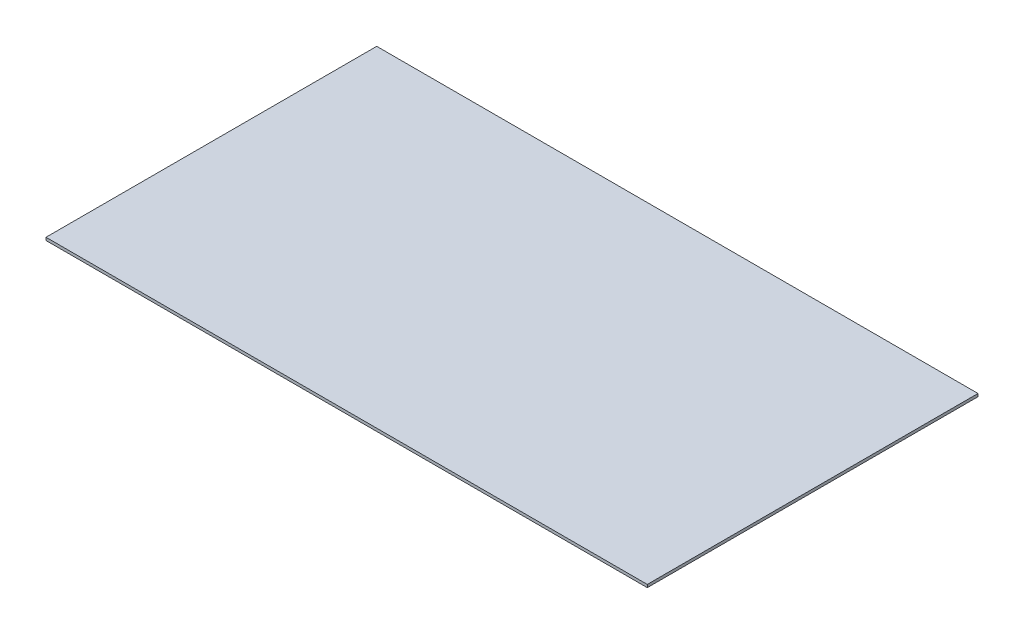
SolidWorks part; units mm, degrees
ref_plane "Front Plane" through (0, 0, 0) normal (0, 0, 1) x (1, 0, 0)
ref_plane "Top Plane" through (0, 0, 0) normal (0, 1, 0) x (1, 0, 0)
ref_plane "Right Plane" through (0, 0, 0) normal (1, 0, 0) x (0, 0, -1)
sketch "Sketch1" plane through (0, 0, 0) normal (0, 1, 0) x (1, 0, 0)
  line L0 (0, -698.5) -> (0, 698.5) construction
  line L1 (-1270, 0) -> (1270, 0) construction
  line L2 (-1270, -698.5) -> (-1270, 698.5)
  line L3 (-1270, 698.5) -> (1270, 698.5)
  line L4 (1270, 698.5) -> (1270, -698.5)
  line L5 (1270, -698.5) -> (-1270, -698.5)
  dimension "D1" = 2540
  dimension "D2" = 1397
extrude "Boss-Extrude1" add sketch "Sketch1" along normal blind 12
